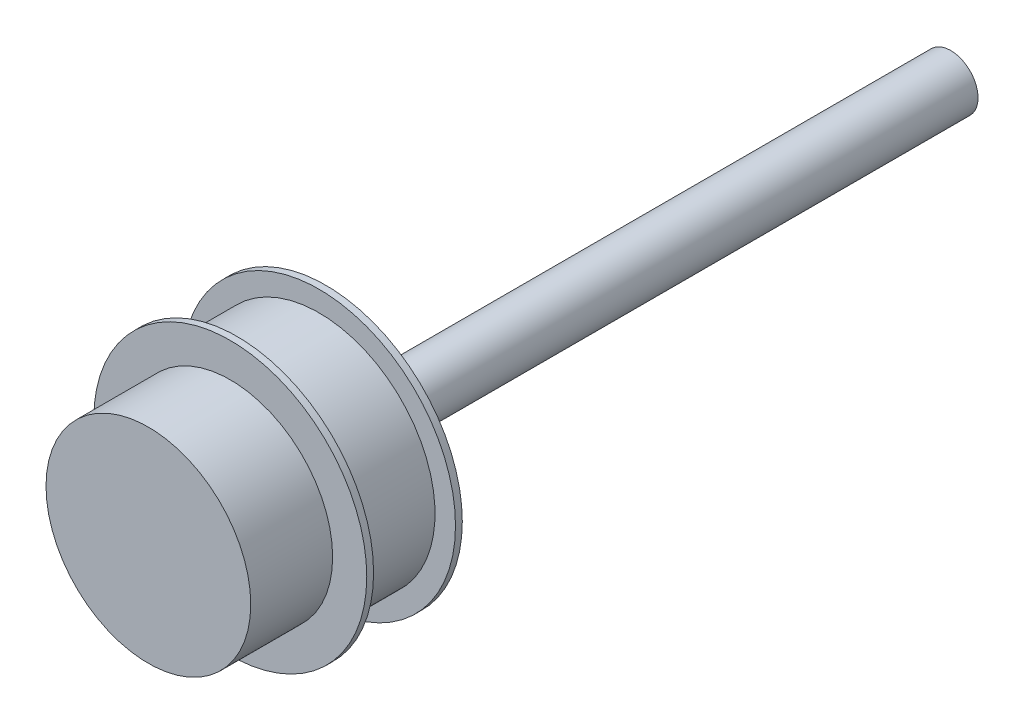
SolidWorks part; units mm, degrees
ref_plane "前视基准面" through (0, 0, 0) normal (0, 0, 1) x (1, 0, 0)
ref_plane "上视基准面" through (0, 0, 0) normal (0, 1, 0) x (1, 0, 0)
ref_plane "右视基准面" through (0, 0, 0) normal (1, 0, 0) x (0, 0, -1)
sketch "草图1" plane through (0, 0, 0) normal (0, 0, 1) x (1, 0, 0)
  circle A0 centre (0, 0) radius 4
extrude "凸台-拉伸1" add sketch "草图1" along normal blind 91.56 contours A0
sketch "草图2" plane through (0, 0, 91.56) normal (0, 0, 1) x (1, 0, 0)
  circle A0 centre (0, 0) radius 20
extrude "凸台-拉伸2" add sketch "草图2" along normal blind 14
sketch "草图3" plane through (0, 0, 105.56) normal (0, 0, 1) x (1, 0, 0)
  circle A0 centre (0, 0) radius 15
extrude "凸台-拉伸3" add sketch "草图3" along normal blind 12
sketch "草图4" plane through (0, 0, 91.56) normal (0, 0, -1) x (-1, 0, 0)
  circle A0 centre (0, 0) radius 17
  circle A1 centre (0, 0) radius 20 construction
  circle A2 centre (0, 0) radius 20
  dimension "D1" = 3
extrude "切除-拉伸1" cut sketch "草图4" against normal blind 13
sketch "草图5" plane through (0, 0, 91.56) normal (0, 0, -1) x (-1, 0, 0)
  circle A0 centre (0, 0) radius 20
extrude "凸台-拉伸4" add sketch "草图5" against normal blind 1
